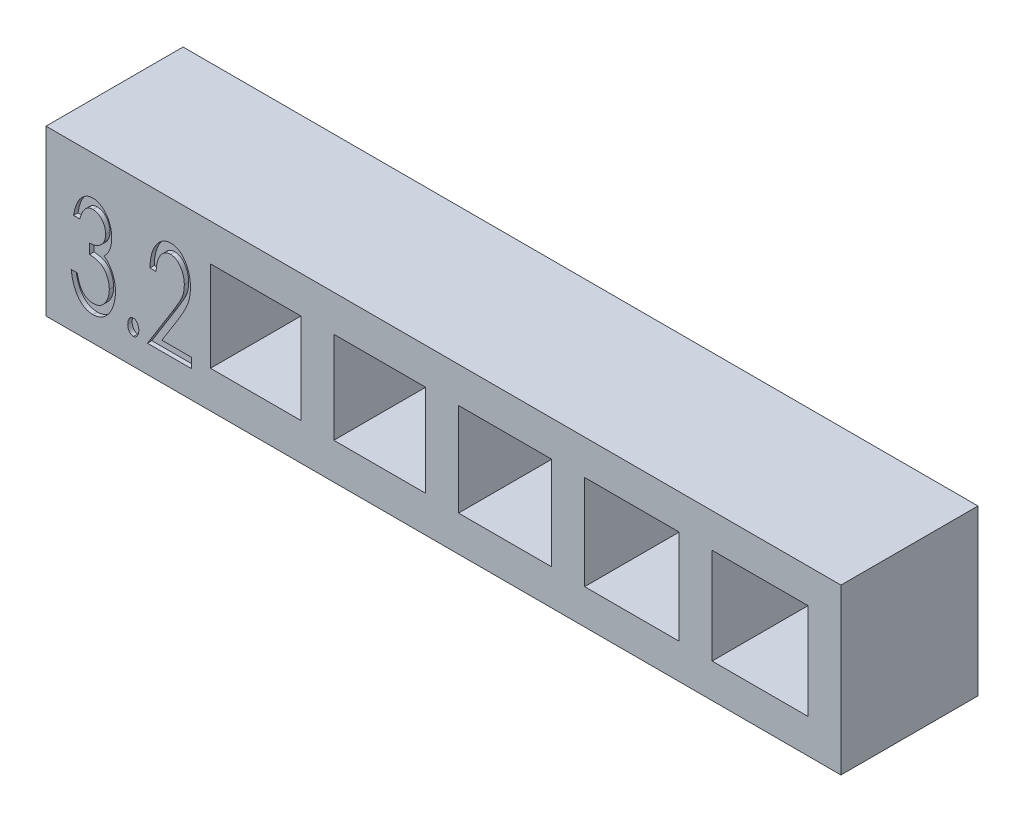
SolidWorks part; units mm, degrees
ref_plane "Front Plane" through (0, 0, 0) normal (0, 0, 1) x (1, 0, 0)
ref_plane "Top Plane" through (0, 0, 0) normal (0, 1, 0) x (1, 0, 0)
ref_plane "Right Plane" through (0, 0, 0) normal (1, 0, 0) x (0, 0, -1)
sketch "Sketch1" plane through (0, 0, 0) normal (0, 0, 1) x (1, 0, 0)
  line L0 (0, 3) -> (29, 3) construction
  line L1 (0, 0) -> (29, 0)
  line L2 (0, 0) -> (0, 6)
  line L3 (0, 6) -> (29, 6)
  line L4 (29, 0) -> (29, 6)
  line L6 (6, 1.35) -> (9.3, 1.35)
  line L7 (6, 1.35) -> (6, 4.65)
  line L8 (6, 4.65) -> (9.3, 4.65)
  line L9 (9.3, 1.35) -> (9.3, 4.65)
  line L10 (6, 1.35) -> (9.3, 4.65) construction
  line L11 (6, 4.65) -> (9.3, 1.35) construction
  line L12 (10.5, 1.325) -> (13.85, 1.325)
  line L13 (10.5, 1.325) -> (10.5, 4.675)
  line L14 (10.5, 4.675) -> (13.85, 4.675)
  line L15 (13.85, 1.325) -> (13.85, 4.675)
  line L16 (10.5, 1.325) -> (13.85, 4.675) construction
  line L17 (10.5, 4.675) -> (13.85, 1.325) construction
  line L18 (15.05, 1.3) -> (18.45, 1.3)
  line L19 (15.05, 1.3) -> (15.05, 4.7)
  line L20 (15.05, 4.7) -> (18.45, 4.7)
  line L21 (18.45, 1.3) -> (18.45, 4.7)
  line L22 (15.05, 1.3) -> (18.45, 4.7) construction
  line L23 (15.05, 4.7) -> (18.45, 1.3) construction
  line L24 (19.65, 1.275) -> (23.1, 1.275)
  line L25 (19.65, 1.275) -> (19.65, 4.725)
  line L26 (19.65, 4.725) -> (23.1, 4.725)
  line L27 (23.1, 1.275) -> (23.1, 4.725)
  line L28 (19.65, 1.275) -> (23.1, 4.725) construction
  line L29 (19.65, 4.725) -> (23.1, 1.275) construction
  line L31 (24.3, 1.25) -> (27.8, 1.25)
  line L32 (24.3, 1.25) -> (24.3, 4.75)
  line L33 (24.3, 4.75) -> (27.8, 4.75)
  line L34 (27.8, 1.25) -> (27.8, 4.75)
  line L35 (24.3, 1.25) -> (27.8, 4.75) construction
  line L36 (24.3, 4.75) -> (27.8, 1.25) construction
  point P7 (7.65, 3)
  point P12 (12.175, 3)
  point P17 (16.75, 3)
  point P22 (21.375, 3)
  point P33 (26.05, 3)
  dimension "D1" = 3.3
  dimension "D2" = 3.35
  dimension "D3" = 3.4
  dimension "D4" = 3.45
  dimension "D5" = 6
  dimension "D6" = 6
  dimension "D7" = 1.2
  dimension "D8" = 1.2
  dimension "D9" = 1.2
  dimension "D10" = 3.5
  dimension "D11" = 1.2
  dimension "D12" = 1.2
extrude "Boss-Extrude1" add sketch "Sketch1" along normal blind 5
sketch "Sketch3" plane through (0, 0, 5) normal (0, 0, 1) x (1, 0, 0)
  text T0 "3.2" font "Century Gothic" height 3.5
  point P1 (1.9671, 2.9169)
  point P2 (0.8281, 0.9913)
extrude "Cut-Extrude1" cut sketch "Sketch3" against normal blind 0.16
